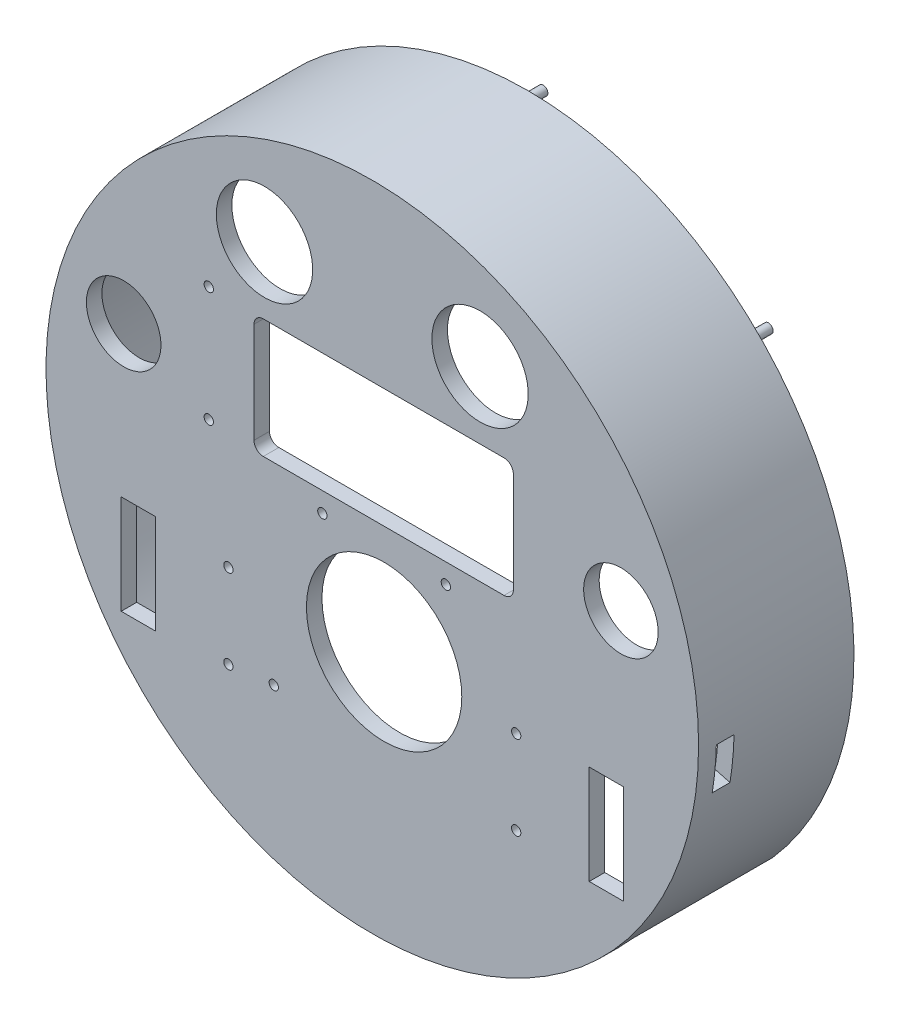
SolidWorks part; units mm, degrees
ref_plane "Plan de face" through (0, 0, 0) normal (0, 0, 1) x (1, 0, 0)
ref_plane "Plan de dessus" through (0, 0, 0) normal (0, 1, 0) x (1, 0, 0)
ref_plane "Plan de droite" through (0, 0, 0) normal (1, 0, 0) x (0, 0, -1)
sketch "Esquisse1" plane through (0, 0, 0) normal (0, 0, 1) x (1, 0, 0)
  circle A0 centre (0, 0) radius 105
  dimension "D1" = 210
extrude "Boss.-Extru.1" add sketch "Esquisse1" along normal blind 50
shell "Coque1" thickness 5
sketch3d "Esquisse3D1"
  line L0 (0, 0, 0) -> (0, 0, 42.8411) construction
  line L1 (0, -105, 0) -> (0, -105, 50) construction
  circle A3 centre (0, 0, 0) radius 105 construction
  circle A4 centre (0, 0, 50) radius 105 construction
  point P3 (0, 0, 0)
  point P9 (0, 0, 105)
  point P12 (0, 0, 155)
sketch "Esquisse3" plane through (0, 0, 45) normal (0, 0, -1) x (-1, 0, 0)
  circle A0 centre (-3.8, -24.5576) radius 25
  circle A1 centre (-23.6695, 4.1345) radius 1.5
  circle A2 centre (16.0695, 4.1345) radius 1.5
  circle A3 centre (31.7, -51.5576) radius 1.5
extrude "Enlèv. mat.-Extru.1" cut sketch "Esquisse3" against normal blind 10
sketch "Esquisse5" plane through (0, 0, 45) normal (0, 0, -1) x (-1, 0, 0)
  line L1 (-42.3889, 10.4726) -> (35.0744, 10.4726)
  line L2 (-45.3889, 13.4726) -> (-45.3889, 45.8069)
  line L3 (-42.3889, 48.8069) -> (35.0744, 48.8069)
  line L4 (38.0744, 13.4726) -> (38.0744, 45.8069)
  arc A0 (35.0744, 48.8069) -> (38.0744, 45.8069) centre (35.0744, 45.8069) cw
  arc A1 (35.0744, 10.4726) -> (38.0744, 13.4726) centre (35.0744, 13.4726) ccw
  arc A2 (-42.3889, 10.4726) -> (-45.3889, 13.4726) centre (-42.3889, 13.4726) cw
  arc A3 (-45.3889, 45.8069) -> (-42.3889, 48.8069) centre (-42.3889, 45.8069) cw
  point P4 (36.8191, 10.4726)
  dimension "D1" = 3
extrude "Enlèv. mat.-Extru.2" cut sketch "Esquisse5" against normal through all
sketch "Esquisse6" plane through (0, 0, 0) normal (0, 0, -1) x (-1, 0, 0)
  line L0 (-78.8107, -69.3821) -> (78.8107, -69.3821)
  line L1 (78.5009, -69.3821) -> (-78.8107, -69.3821) construction
  circle A0 centre (0, 0) radius 105 construction
  arc A1 (-78.8107, -69.3821) -> (78.8107, -69.3821) centre (0, 0) ccw
extrude "Enlèv. mat.-Extru.3" cut sketch "Esquisse6" against normal blind 45
sketch "Esquisse7" plane through (0, 0, 45) normal (0, 0, -1) x (-1, 0, 0)
  circle A0 centre (52.6142, 48.9901) radius 1.5
  circle A1 centre (52.6142, 11.9901) radius 1.5
  circle A2 centre (46.3, -26.0576) radius 1.5
  circle A3 centre (46.3, -53.0576) radius 1.5
  circle A4 centre (-46.3, -26.0622) radius 1.5
  circle A5 centre (-46.3, -53.0622) radius 1.5
extrude "Enlèv. mat.-Extru.4" cut sketch "Esquisse7" against normal through all
sketch "Esquisse8" plane through (0, 0, 45) normal (0, 0, -1) x (-1, 0, 0)
  line L0 (0, 116.3573) -> (0, -138.2334) construction
  line L7 (-80.8, -55.5371) -> (-80.8, -23.6417)
  line L8 (-80.8, -23.6417) -> (-69.8, -23.6417)
  line L9 (-69.8, -55.5371) -> (-69.8, -23.6417)
  line L10 (-80.8, -55.5371) -> (-69.8, -55.5371)
  line L11 (80.8, -55.5371) -> (69.8, -55.5371)
  line L12 (69.8, -55.5371) -> (69.8, -23.6417)
  line L13 (80.8, -23.6417) -> (69.8, -23.6417)
  line L14 (80.8, -55.5371) -> (80.8, -23.6417)
extrude "Enlèv. mat.-Extru.5" cut sketch "Esquisse8" against normal blind 5
sketch "Esquisse9" plane through (0, 0, 45) normal (0, 0, -1) x (-1, 0, 0)
  circle A2 centre (34.6819, 70.4401) radius 15.5
  circle A3 centre (-34.6819, 70.4401) radius 15.5
extrude "Enlèv. mat.-Extru.7" cut sketch "Esquisse9" against normal through all
sketch "Esquisse10" plane through (-9.6819, 0.4401, 22) normal (0, 0, -1) x (-1, 0, 0)
  line L1 (-43.2214, 88.9656) -> (-42.9259, 93.8724)
  line L2 (-41.7241, 88.8754) -> (-44.7187, 89.0558) construction
  arc A0 (62.3329, -69.8221) -> (-81.6967, -69.8221) centre (-9.6819, -0.4401) ccw construction
sweep "Balayage1" add path "Esquisse10" circular profile diameter 3 parameters "D3"=3
sketch "Esquisse19" plane through (-5.54, 91.9764, 0) normal (-0.0601, 0.9982, 0) x (0.9982, 0.0601, 0)
  line L1 (38.8542, -23.5) -> (38.8542, -20.5)
  line L2 (38.8542, -23.5) -> (38.8542, -20.5)
  arc A1 (38.8542, -20.5) -> (38.8542, -23.5) centre (38.8542, -22) ccw
  arc A2 (38.8542, -20.5) -> (38.8542, -23.5) centre (38.8542, -22) ccw
  dimension "D1" = 0
extrude "Boss.-Extru.2" add sketch "Esquisse19" along normal blind 1
sketch "Esquisse20" plane through (-9.6819, 0.4401, 22) normal (0, 0, -1) x (-1, 0, 0)
  line L0 (-73.3113, 71.7436) -> (-78.4695, 72.1427)
  line L1 (-73.2211, 73.2409) -> (-73.4015, 70.2463) construction
  arc A0 (62.3329, -69.8221) -> (-81.6967, -69.8221) centre (-9.6819, -0.4401) ccw construction
  point P4 (0, 0)
sweep "Balayage2" add path "Esquisse20" circular profile diameter 3 parameters "D3"=3
sketch "Esquisse27" plane through (73.961, 5.7229, 0) normal (0.997, 0.0771, 0) x (0, 0, -1)
  line L1 (-20.5, 67.0598) -> (-23.5, 67.0598)
  line L2 (-20.5, 67.0598) -> (-23.5, 67.0598)
  arc A1 (-23.5, 67.0598) -> (-20.5, 67.0598) centre (-22, 67.0598) ccw
  arc A2 (-23.5, 67.0598) -> (-20.5, 67.0598) centre (-22, 67.0598) ccw
  dimension "D1" = 0
extrude "Boss.-Extru.3" add sketch "Esquisse27" along normal blind 2
mirror "Symétrie1" about plane through (0, 0, 0) normal (1, 0, 0) of "Balayage1", "Boss.-Extru.2", "Balayage2", "Boss.-Extru.3"
sketch "Esquisse30" plane through (0, 0, 0) normal (0, 0, -1) x (-1, 0, 0)
  line L2 (0, 145.1425) -> (0, 39.277) construction
  line L3 (0, 0) -> (-72.4784, 72.4784) construction
  line L4 (-78.8107, -69.3821) -> (-72.0148, -69.3821)
  line L5 (72.0148, -69.3821) -> (78.8107, -69.3821)
  line L6 (-78.8107, -69.3821) -> (-72.0148, -69.3821)
  line L7 (72.0148, -69.3821) -> (78.8107, -69.3821)
  arc A4 (78.8107, -69.3821) -> (-78.8107, -69.3821) centre (0, 0) ccw
  arc A5 (72.0148, -69.3821) -> (-72.0148, -69.3821) centre (0, 0) ccw
  circle A10 centre (0, 102.5) radius 1.5
  arc A11 (73.8152, -71.1166) -> (-73.8152, -71.1166) centre (0, 0) ccw
  arc A12 (73.8152, -71.1166) -> (-73.8152, -71.1166) centre (0, 0) ccw
  circle A13 centre (-72.4784, 72.4784) radius 1.5
  circle A14 centre (72.4784, 72.4784) radius 1.5
  dimension "D3" = 3
  dimension "D5" = 3
  dimension "D4" = 45
  dimension "D1" = 0
  dimension "D2" = 2.5
extrude "Boss.-Extru.4" add sketch "Esquisse30" along normal blind 5
sketch "Esquisse31" plane through (0, 0, 45) normal (0, 0, -1) x (-1, 0, 0)
  circle A0 centre (-80, 25) radius 12
  circle A1 centre (80, 25) radius 12
extrude "Enlèv. mat.-Extru.8" cut sketch "Esquisse31" against normal blind 5
sketch "Esquisse32" plane through (91.9851, -26.8015, -210) normal (0.9659, -0.2588, 0) x (0, 0, -1)
  line L1 (-254.2642, 26.6025) -> (-248.5508, 26.6025)
  line L2 (-254.2642, 26.6025) -> (-254.2642, 12.716)
  line L3 (-254.2642, 12.716) -> (-248.5508, 12.716)
  line L4 (-248.5508, 26.6025) -> (-248.5508, 12.716)
  line L5 (-254.2642, 26.6025) -> (-248.5508, 12.716) construction
  line L6 (-254.2642, 12.716) -> (-248.5508, 26.6025) construction
  point P0 (-251.4075, 19.6592)
  point P5 (-246.1019, 11.2804)
  point P6 (-248.5508, 12.716)
extrude "Enlèv. mat.-Extru.10" cut sketch "Esquisse32" along normal through all
